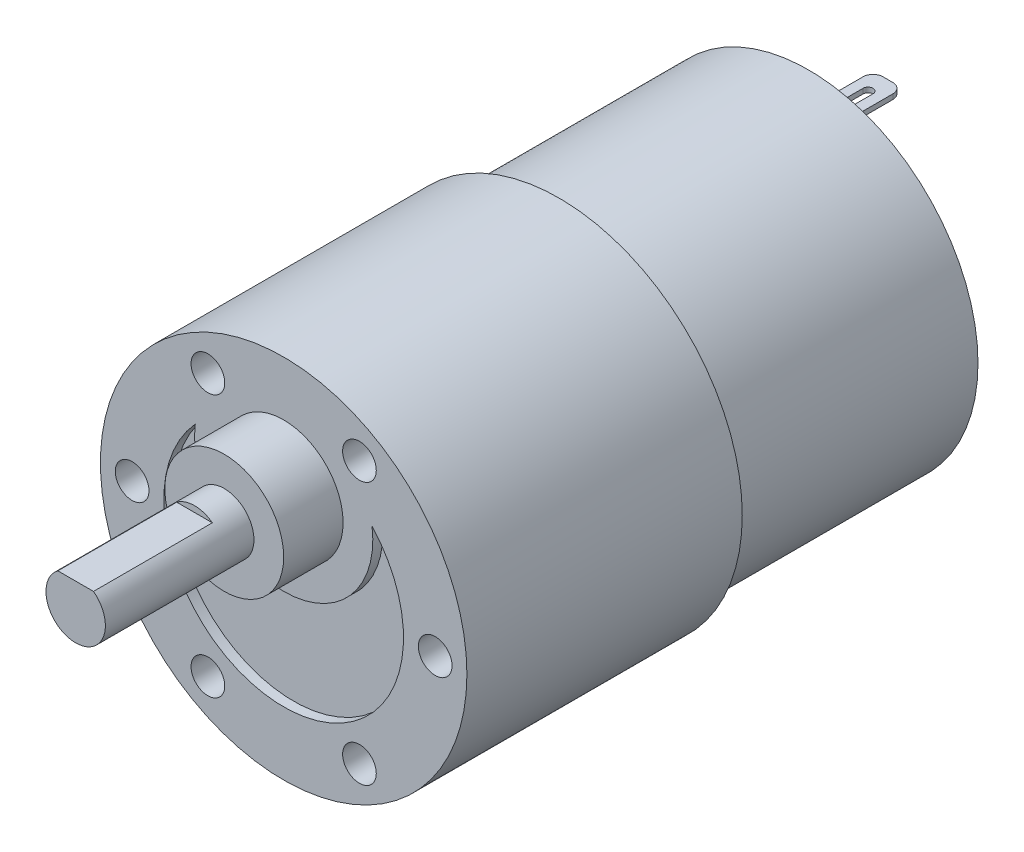
SolidWorks part; units mm, degrees
ref_plane "Front Plane" through (0, 0, 0) normal (0, 0, 1) x (1, 0, 0)
ref_plane "Top Plane" through (0, 0, 0) normal (0, 1, 0) x (1, 0, 0)
ref_plane "Right Plane" through (0, 0, 0) normal (1, 0, 0) x (0, 0, -1)
sketch "Sketch1" plane through (0, 0, 0) normal (0, 0, 1) x (1, 0, 0)
  circle A0 centre (0, 0) radius 18.5
  dimension "D1" = 37
extrude "Boss-Extrude1" add sketch "Sketch1" along normal blind 27.8
sketch "Sketch2" plane through (0, 0, 0) normal (0, 0, -1) x (-1, 0, 0)
  circle A0 centre (0, 0) radius 17.1
  dimension "D1" = 34.2
extrude "Boss-Extrude2" add sketch "Sketch2" along normal blind 25.2
sketch "Sketch3" plane through (0, 0, -25.2) normal (0, 0, -1) x (-1, 0, 0)
  circle A0 centre (0, 0) radius 3.75
  dimension "D1" = 7.5
extrude "Boss-Extrude3" add sketch "Sketch3" along normal blind 3.3
sketch "Sketch4" plane through (0, 0, 27.8) normal (0, 0, 1) x (1, 0, 0)
  circle A0 centre (0, 7) radius 6
  circle A1 centre (0, 0) radius 18.5 construction
  dimension "D1" = 12
  dimension "D2" = 7
extrude "Boss-Extrude4" add sketch "Sketch4" along normal blind 6
sketch "Sketch5" plane through (0, 0, 33.8) normal (0, 0, 1) x (1, 0, 0)
  circle A0 centre (0, 7) radius 3
  dimension "D1" = 6
extrude "Boss-Extrude6" add sketch "Sketch5" along normal blind 15
sketch "Sketch7" plane through (0, 0, 48.8) normal (0, 0, 1) x (1, 0, 0)
  line L0 (-1.8, 9.4) -> (1.8, 9.4)
  line L1 (0, 7) -> (0, 9.4) construction
  arc A1 (-1.8, 9.4) -> (1.8, 9.4) centre (0, 7) cw
  dimension "D2" = 2.4
extrude "Cut-Extrude1" cut sketch "Sketch7" against normal blind 12
sketch "Sketch8" plane through (0, 0, 27.8) normal (0, 0, 1) x (1, 0, 0)
  circle A0 centre (0, 0) radius 18.5 construction
  arc A1 (8.9233, 8.1721) -> (-8.9233, 8.1721) centre (0, 0) cw
  arc A3 (-8.9233, 8.1721) -> (8.9233, 8.1721) centre (0, 7) ccw
  dimension "D1" = 9
  dimension "D2" = 12.1
  dimension "D3" = 6.4
  dimension "D4" = 7
extrude "Cut-Extrude2" cut sketch "Sketch8" against normal blind 1
hole_wizard "M3 Clearance Hole1" positions "Sketch9" profile "Sketch10" hole size "M3" standard "ANSI Metric"
sketch "Sketch9" plane through (0, 0, 27.8) normal (0, 0, 1) x (1, 0, 0)
  line L0 (0, 0) -> (0, -7.0626) construction
  line L2 (7.65, -13.2502) -> (0, 0) construction
  line L3 (-7.65, -13.2502) -> (0, 0) construction
  line L5 (-15.3, 0) -> (0, 0) construction
  line L6 (0, 0) -> (-7.65, 13.2502) construction
  line L8 (0, 0) -> (15.3, 0) construction
  line L9 (0, 0) -> (7.65, 13.2502) construction
  circle A0 centre (0, 0) radius 15.3
  point P0 (7.65, -13.2502)
  point P23 (-7.65, -13.2502)
  point P25 (-15.3, 0)
  point P27 (-7.65, 13.2502)
  point P32 (15.3, 0)
  point P60 (7.65, 13.2502)
  dimension "D1" = 15.3
  dimension "D2" = 30
  dimension "D3" = 30
  dimension "D4" = 60
  dimension "D5" = 60
  dimension "D6" = 60
  dimension "D7" = 60
sketch "Sketch10" plane through (7.65, -13.2502, 27.8) normal (1, 0, 0) x (0, -1, 0)
  line L0 (0, 0) -> (0, 7.0215)
  line L1 (0, 7.0215) -> (1.7, 6)
  line L2 (1.7, 6) -> (1.7, 0)
  line L5 (1.7, 0) -> (0, 0)
  line L10 (0, 7.0215) -> (-1.7, 6) construction
  line L11 (0, -6.35) -> (0, 107.95) construction
  dimension "Hole Dia." = 3.4
  dimension "Hole Depth" = 6
  dimension "Drill Angle" = 118
sketch "Sketch11" plane through (0, 0, -25.2) normal (0, 0, -1) x (-1, 0, 0)
  line L0 (0, 0) -> (-11.6852, 0) construction
  line L1 (-1.5, 12.25) -> (1.5, 12.25)
  line L2 (-1.5, 12.25) -> (-1.5, 11.75)
  line L3 (-1.5, 11.75) -> (1.5, 11.75)
  line L4 (1.5, 12.25) -> (1.5, 11.75)
  line L5 (-1.5, 12.25) -> (1.5, 11.75) construction
  line L6 (-1.5, 11.75) -> (1.5, 12.25) construction
  line L7 (-1.5, -12.25) -> (-1.5, -11.75)
  line L8 (1.5, -12.25) -> (1.5, -11.75)
  line L9 (-1.5, -12.25) -> (1.5, -12.25)
  line L10 (-1.5, -11.75) -> (1.5, -11.75)
  point P0 (0, 12)
  point P8 (-1.5, 12)
  point P13 (-1.5, -12)
  dimension "D1" = 12
  dimension "D2" = 0
  dimension "D3" = 0.5
  dimension "D4" = 3
extrude "Boss-Extrude7" add sketch "Sketch11" along normal blind 8
fillet "Fillet1" radius 1 4 edges at (1.5, -12, -33.2) (-1.5, -12, -33.2) (-1.5, 12, -33.2) (1.5, 12, -33.2)
sketch "Sketch12" plane through (0, 12.25, 0) normal (0, 1, 0) x (1, 0, 0)
  line L0 (0, 31.2) -> (0, 29.2) construction
  line L1 (0.4921, 31.2) -> (0.4921, 29.2)
  line L2 (-0.4921, 31.2) -> (-0.4921, 29.2)
  line L3 (-1.5, 32.2) -> (-1.5, 25.2) construction
  line L4 (-0.5, 33.2) -> (0.5, 33.2) construction
  arc A0 (0.4921, 31.2) -> (-0.4921, 31.2) centre (0, 31.2) ccw
  arc A1 (-0.4921, 29.2) -> (0.4921, 29.2) centre (0, 29.2) ccw
  point P2 (0, 30.2)
  dimension "D1" = 2
  dimension "D2" = 1.5
  dimension "D3" = 2
extrude "Cut-Extrude3" cut sketch "Sketch12" against normal blind 28
